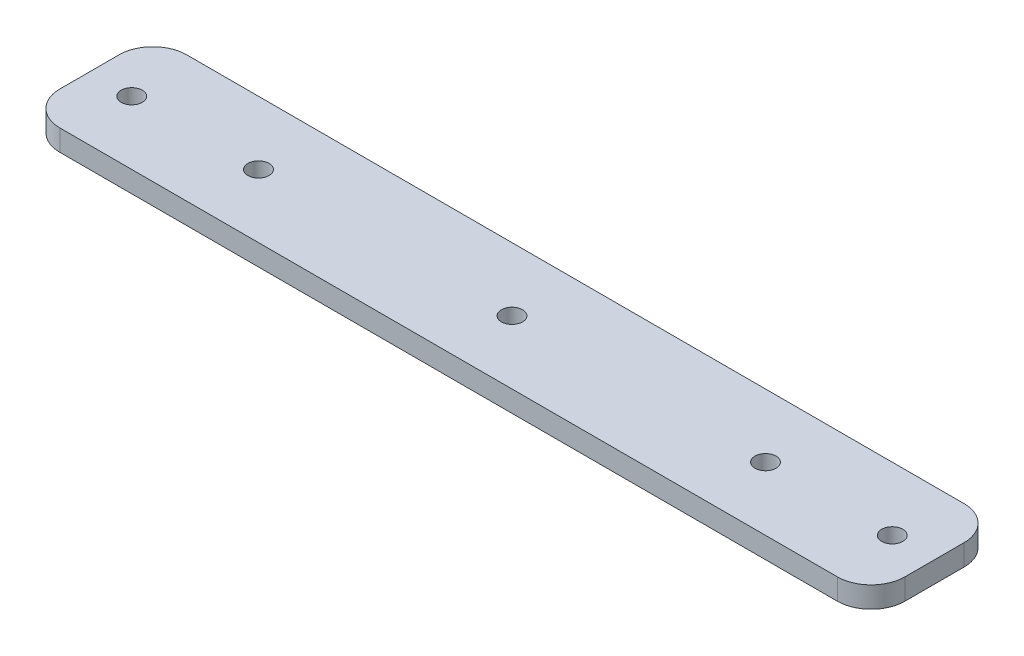
SolidWorks part; units mm, degrees
ref_plane "Front Plane" through (0, 0, 0) normal (0, 0, 1) x (1, 0, 0)
ref_plane "Top Plane" through (0, 0, 0) normal (0, 1, 0) x (1, 0, 0)
ref_plane "Right Plane" through (0, 0, 0) normal (1, 0, 0) x (0, 0, -1)
sketch "Sketch2" plane through (0, 0, 0) normal (0, 1, 0) x (1, 0, 0)
  line L1 (10.16, 0) -> (243.84, 0)
  line L2 (0, -10.16) -> (0, -27.94)
  line L3 (10.16, -38.1) -> (243.84, -38.1)
  line L4 (254, -10.16) -> (254, -27.94)
  circle A0 centre (12.7, -19.05) radius 3.175
  circle A1 centre (241.3, -19.05) radius 3.175
  circle A2 centre (50.8, -19.05) radius 3.175
  circle A3 centre (127, -19.05) radius 3.175
  circle A4 centre (203.2, -19.05) radius 3.175
  arc A5 (243.84, -38.1) -> (254, -27.94) centre (243.84, -27.94) ccw
  arc A6 (254, -10.16) -> (243.84, 0) centre (243.84, -10.16) ccw
  arc A7 (0, -27.94) -> (10.16, -38.1) centre (10.16, -27.94) ccw
  arc A8 (0, -10.16) -> (10.16, 0) centre (10.16, -10.16) cw
  point P19 (254, 0)
  point P24 (0, 0)
  point P25 (0, 0)
  dimension "D1" = 254
  dimension "D2" = 10.16
extrude "Boss-Extrude1" add sketch "Sketch2" along normal blind 6.35
